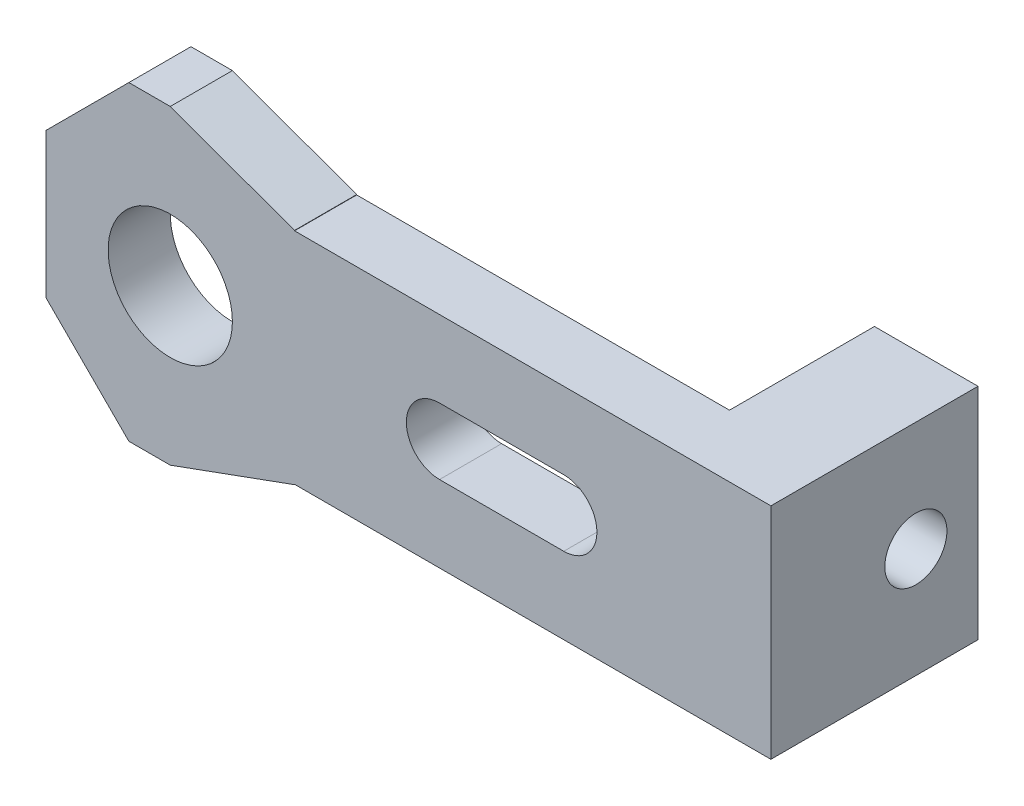
SolidWorks part; units mm, degrees
material "AISI 1015 Acier étiré à froid (SS)"
ref_plane "Plan de face" through (0, 0, 0) normal (0, 0, 1) x (1, 0, 0)
ref_plane "Plan de dessus" through (0, 0, 0) normal (0, 1, 0) x (1, 0, 0)
ref_plane "Plan de droite" through (0, 0, 0) normal (1, 0, 0) x (0, 0, -1)
sketch "Esquisse1" plane through (0, 0, 0) normal (0, 0, 1) x (1, 0, 0)
  line L1 (0, 0) -> (35, 0)
  line L2 (0, 0) -> (0, 15)
  line L3 (0, 15) -> (35, 15)
  line L4 (35, 0) -> (35, 15)
  dimension "D1" = 15
  dimension "D2" = 35
extrude "Boss.-Extru.1" add sketch "Esquisse1" along normal blind 3
sketch "Esquisse4" plane through (0, 0, 3) normal (0, 0, 1) x (1, 0, 0)
  line L0 (0, 15) -> (0, 0) construction
  circle A0 centre (6, 7.5) radius 3
  point P4 (0, 7.5)
  dimension "D2" = 6
  dimension "D1" = 6
extrude "Enlèv. mat.-Extru.1" cut sketch "Esquisse4" against normal through all
chamfer "Chanfrein1" distance 4 angle 45 2 edges at (0, 0, 1.5) (0, 15, 1.5)
sketch "Esquisse5" plane through (0, 0, 0) normal (0, 0, -1) x (-1, 0, 0)
  line L0 (-19, 7.5) -> (-25, 7.5) construction
  line L1 (-19, 5.9) -> (-25, 5.9)
  line L2 (-19, 9.1) -> (-25, 9.1)
  line L4 (-4, 0) -> (-35, 0) construction
  line L6 (-35, 15) -> (-4, 15) construction
  line L9 (0, 11) -> (0, 4) construction
  arc A0 (-19, 5.9) -> (-19, 9.1) centre (-19, 7.5) ccw
  arc A1 (-25, 9.1) -> (-25, 5.9) centre (-25, 7.5) ccw
  point P2 (-22, 7.5)
  dimension "D1" = 1.6
  dimension "D2" = 6
  dimension "D4" = 19
extrude "Enlèv. mat.-Extru.2" cut sketch "Esquisse5" against normal through all
sketch "Esquisse6" plane through (0, 0, 0) normal (0, 0, -1) x (-1, 0, 0)
  line L0 (-35, 15) -> (-4, 15) construction
  line L1 (-35, 0) -> (-30, 0)
  line L2 (-35, 0) -> (-35, 15)
  line L3 (-35, 15) -> (-30, 15)
  line L4 (-30, 0) -> (-30, 15)
  dimension "D1" = 5
extrude "Boss.-Extru.2" add sketch "Esquisse6" along normal blind 7
sketch "Esquisse7" plane through (0, 0, -7) normal (0, 0, -1) x (-1, 0, 0)
  line L0 (-25, 7.5) -> (-35, 7.5) construction
  line L1 (-35, 0) -> (-12, 0)
  line L2 (-35, 0) -> (-35, 2.2)
  line L3 (-35, 2.2) -> (-12, 2.2)
  line L4 (-12, 0) -> (-12, 2.2)
  line L5 (-35, 15) -> (-35, 0) construction
  line L6 (-12, 15) -> (-12, 12.8)
  line L7 (-35, 12.8) -> (-12, 12.8)
  line L8 (-35, 15) -> (-35, 12.8)
  line L9 (-35, 15) -> (-12, 15)
  point P14 (-35, 1.1)
  dimension "D1" = 10.6
  dimension "D2" = 23
extrude "Enlèv. mat.-Extru.3" cut sketch "Esquisse7" against normal through all
chamfer "Chanfrein2" distance 6 angle 20 2 edges at (12, 15, 1.5) (12, 0, 1.5)
sketch "Esquisse8" plane through (30, 0, 0) normal (-1, 0, 0) x (0, 0, 1)
  line L0 (-3.2819, 7.5) -> (-6.5869, 7.5) construction
  line L3 (-7, 2.2) -> (0, 2.2) construction
  line L4 (0, 12.8) -> (-7, 12.8) construction
  line L5 (-7, 2.2) -> (-7, 12.8) construction
  circle A0 centre (-4, 7.5) radius 1.5
  dimension "D1" = 3
  dimension "D2" = 3
extrude "Enlèv. mat.-Extru.4" cut sketch "Esquisse8" against normal blind 7
